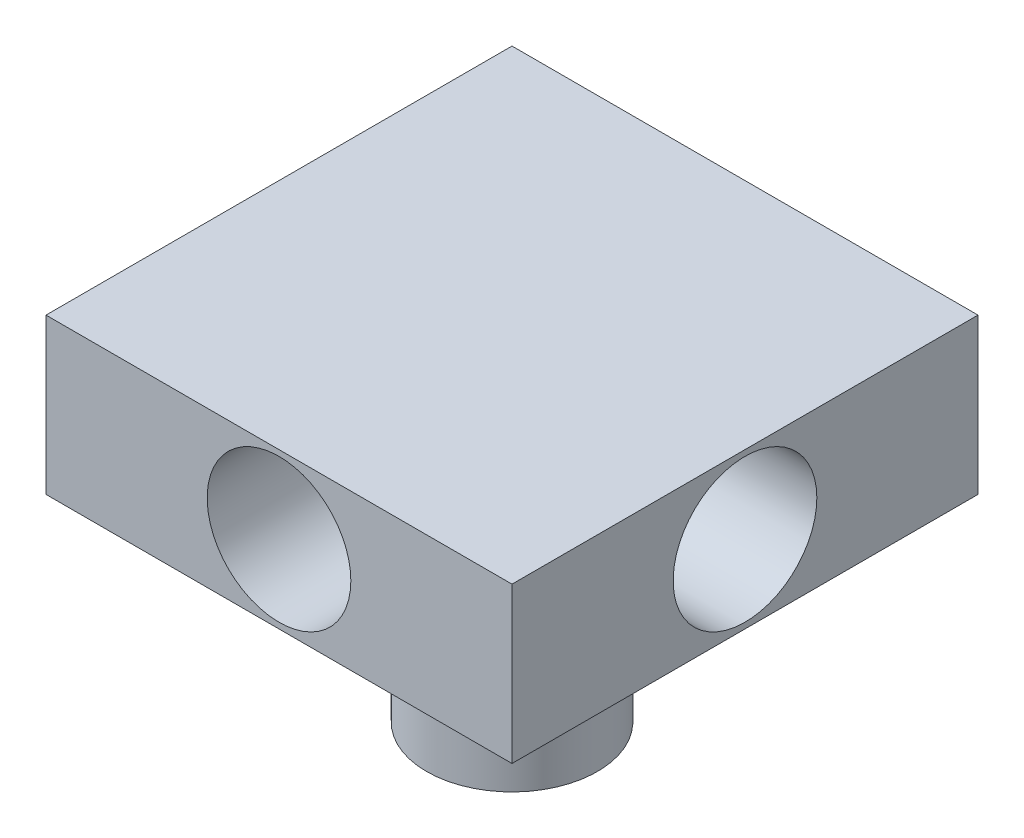
SolidWorks part; units mm, degrees
ref_plane "Front Plane" through (0, 0, 0) normal (0, 0, 1) x (1, 0, 0)
ref_plane "Top Plane" through (0, 0, 0) normal (0, 1, 0) x (1, 0, 0)
ref_plane "Right Plane" through (0, 0, 0) normal (1, 0, 0) x (0, 0, -1)
sketch "Sketch1" plane through (0, 0, 0) normal (0, 1, 0) x (1, 0, 0)
  circle A0 centre (0, 0) radius 11
  dimension "D1" = 22
extrude "Boss-Extrude1" add sketch "Sketch1" along normal blind 25.4
sketch "Sketch13" plane through (0, 25.4, 0) normal (0, 1, 0) x (1, 0, 0)
  line L1 (30, -30) -> (-30, -30)
  line L2 (30, -30) -> (30, 30)
  line L3 (30, 30) -> (-30, 30)
  line L4 (-30, -30) -> (-30, 30)
  line L5 (30, -30) -> (-30, 30) construction
  line L6 (30, 30) -> (-30, -30) construction
  point P0 (0, 0)
  dimension "D1" = 60
  dimension "D2" = 60
extrude "Boss-Extrude5" add sketch "Sketch13" along normal blind 20
sketch "Face 1" plane through (0, 0, 30) normal (0, 0, 1) x (1, 0, 0)
  line L0 (0, 25.4) -> (0, 45.4) construction
  line L1 (-30, 25.4) -> (30, 25.4) construction
  line L2 (-30, 45.4) -> (30, 45.4) construction
  circle A0 centre (0, 35.4) radius 9.25
sketch "Face 2" plane through (30, 0, 0) normal (1, 0, 0) x (0, 0, -1)
  line L0 (0, 25.4) -> (0, 45.4) construction
  line L1 (-30, 25.4) -> (30, 25.4) construction
  line L2 (-30, 45.4) -> (30, 45.4) construction
  circle A0 centre (0, 35.4) radius 9.25
  dimension "D1" = 18.5
sketch "Face 3" plane through (-30, 0, 0) normal (-1, 0, 0) x (0, 0, 1)
  line L0 (0, 25.4) -> (0, 45.4) construction
  line L1 (-30, 25.4) -> (30, 25.4) construction
  line L2 (-30, 45.4) -> (30, 45.4) construction
  circle A0 centre (0, 35.4) radius 9.25
  dimension "D1" = 18.5
extrude "Cut-Extrude1" cut sketch "Face 1" against normal blind 20
extrude "Cut-Extrude2" cut sketch "Face 3" against normal blind 20
extrude "Cut-Extrude3" cut sketch "Face 2" against normal blind 20
